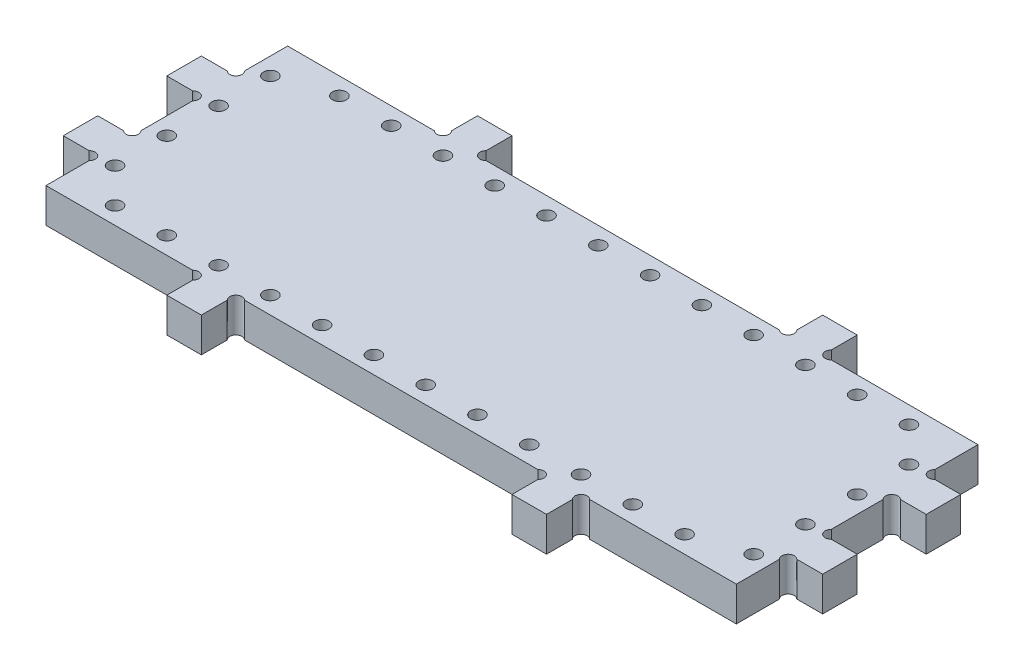
SolidWorks part; units mm, degrees
material "6061 Alloy"
ref_plane "Front" through (0, 0, 0) normal (0, 0, 1) x (1, 0, 0)
ref_plane "Top" through (0, 0, 0) normal (0, 1, 0) x (1, 0, 0)
ref_plane "Right" through (0, 0, 0) normal (1, 0, 0) x (0, 0, -1)
sketch "Sketch2" plane through (0, 0, 0) normal (0, 1, 0) x (1, 0, 0)
  line L1 (-127, -44.45) -> (127, -44.45)
  line L2 (-127, -44.45) -> (-127, 44.45)
  line L3 (-127, 44.45) -> (127, 44.45)
  line L4 (127, -44.45) -> (127, 44.45)
  line L5 (-127, -44.45) -> (127, 44.45) construction
  line L6 (-127, 44.45) -> (127, -44.45) construction
  point P0 (0, 0)
  dimension "D1" = 254
  dimension "D2" = 88.9
extrude "Rectangle Extrusion" add sketch "Sketch2" along normal blind 12.7
sketch "Sketch4" plane through (0, 0, 44.45) normal (0, 0, 1) x (1, 0, 0)
  line L0 (-127, 12.7) -> (-63.5, 12.7) construction
  line L1 (-127, 12.7) -> (127, 12.7) construction
  line L2 (-63.5, 12.7) -> (-63.5, 6.35) construction
  line L3 (-127, 0) -> (127, 0) construction
  line L4 (-57.15, 12.7) -> (-69.85, 12.7)
  line L5 (-57.15, 12.7) -> (-57.15, 0)
  line L6 (-57.15, 0) -> (-69.85, 0)
  line L7 (-69.85, 12.7) -> (-69.85, 0)
  line L8 (-57.15, 12.7) -> (-69.85, 0) construction
  line L9 (-57.15, 0) -> (-69.85, 12.7) construction
  line L10 (0, 12.7) -> (0, 0) construction
  line L11 (57.15, 0) -> (69.85, 0)
  line L12 (69.85, 12.7) -> (69.85, 0)
  line L13 (57.15, 12.7) -> (69.85, 12.7)
  line L14 (57.15, 12.7) -> (57.15, 0)
  dimension "D1" = 63.5
  dimension "D2" = 6.35
  dimension "D3" = 12.7
extrude "Front Face Tabs" add sketch "Sketch4" along normal blind 12.7
mirror "Mirror Rear Face Tabs" about plane through (0, 0, 0) normal (0, 0, 1) of "Front Face Tabs"
sketch "Sketch6" plane through (0, 12.7, 0) normal (0, 1, 0) x (1, 0, 0)
  line L0 (-69.85, 44.45) -> (-127, 44.45) construction
  line L1 (-69.85, 57.15) -> (-69.85, 44.45) construction
  line L2 (-63.5, 57.15) -> (-63.5, 50.1421) construction
  line L3 (-57.15, 57.15) -> (-69.85, 57.15) construction
  line L4 (0, -6.985) -> (0, 6.985) construction
  line L5 (-6.985, 0) -> (6.985, 0) construction
  circle A0 centre (-71.4375, 46.0375) radius 2.2454
  circle A1 centre (-55.5625, 46.0375) radius 2.2454
  circle A2 centre (55.5625, 46.0375) radius 2.2454
  circle A3 centre (71.4375, 46.0375) radius 2.2454
  circle A4 centre (71.4375, -46.0375) radius 2.2454
  circle A5 centre (55.5625, -46.0375) radius 2.2454
  circle A6 centre (-55.5625, -46.0375) radius 2.2454
  circle A7 centre (-71.4375, -46.0375) radius 2.2454
  dimension "D1" = 1.5875
  dimension "D3" = 4.4907
  dimension "D2" = 1.5875
extrude "Tab Curve Front Back" cut sketch "Sketch6" against normal up to surface (12.7 mm away) up to face at (0, 0, 0)
sketch "Sketch7" plane through (127, 0, 0) normal (1, 0, 0) x (0, 0, -1)
  line L0 (-44.45, 12.7) -> (-19.05, 12.7) construction
  line L1 (-44.45, 12.7) -> (44.45, 12.7) construction
  line L2 (-19.05, 12.7) -> (-19.05, 0) construction
  line L3 (66.3575, 0) -> (-66.3575, 0) construction
  line L4 (0, 6.985) -> (0, -6.985) construction
  line L5 (-25.4, 12.7) -> (-12.7, 12.7)
  line L6 (-25.4, 12.7) -> (-25.4, 0)
  line L7 (-25.4, 0) -> (-12.7, 0)
  line L8 (-12.7, 12.7) -> (-12.7, 0)
  line L9 (-25.4, 12.7) -> (-12.7, 0) construction
  line L10 (-25.4, 0) -> (-12.7, 12.7) construction
  line L11 (25.4, 0) -> (12.7, 0)
  line L12 (12.7, 12.7) -> (12.7, 0)
  line L13 (25.4, 12.7) -> (12.7, 12.7)
  line L14 (25.4, 12.7) -> (25.4, 0)
  point P5 (-19.05, 6.35)
  dimension "D1" = 25.4
  dimension "D2" = 12.7
extrude "Right Face Tabs" add sketch "Sketch7" along normal blind 12.7
mirror "Mirror Left Face Tabs" about plane through (0, 0, 0) normal (1, 0, 0) of "Right Face Tabs"
sketch "Sketch8" plane through (0, 12.7, 0) normal (0, 1, 0) x (1, 0, 0)
  line L0 (139.7, 25.4) -> (127, 25.4) construction
  line L1 (127, 25.4) -> (127, 44.45) construction
  line L2 (139.7, 19.05) -> (126.2032, 19.05) construction
  line L3 (139.7, 25.4) -> (139.7, 12.7) construction
  line L4 (-6.985, 0) -> (6.985, 0) construction
  line L5 (0, -6.985) -> (0, 6.985) construction
  circle A0 centre (128.5875, 26.9875) radius 2.2454
  circle A1 centre (128.5875, 11.1125) radius 2.2454
  circle A2 centre (128.5875, -11.1125) radius 2.2454
  circle A3 centre (128.5875, -26.9875) radius 2.2454
  circle A4 centre (-128.5875, -26.9875) radius 2.2454
  circle A5 centre (-128.5875, -11.1125) radius 2.2454
  circle A6 centre (-128.5875, 11.1125) radius 2.2454
  circle A7 centre (-128.5875, 26.9875) radius 2.2454
  dimension "D3" = 4.4907
  dimension "D1" = 1.5875
  dimension "D2" = 1.5875
extrude "Tab Curve Left Right" cut sketch "Sketch8" against normal up to surface (12.7 mm away) up to face at (0, 0, 0)
sketch "Sketch9" plane through (0, 0, 0) normal (0, -1, 0) x (1, 0, 0)
  circle A0 centre (-107.95, 38.1) radius 2.5527
  circle A1 centre (-120.65, 25.4) radius 2.5527
  circle A2 centre (-120.65, 6.35) radius 2.5527
  circle A3 centre (-120.65, -12.7) radius 2.5527
  circle A4 centre (-120.65, -31.75) radius 2.5527
  circle A5 centre (-88.9, 38.1) radius 2.5527
  circle A6 centre (-69.85, 38.1) radius 2.5527
  circle A7 centre (-50.8, 38.1) radius 2.5527
  circle A8 centre (-31.75, 38.1) radius 2.5527
  circle A9 centre (-12.7, 38.1) radius 2.5527
  circle A10 centre (6.35, 38.1) radius 2.5527
  circle A11 centre (25.4, 38.1) radius 2.5527
  circle A12 centre (44.45, 38.1) radius 2.5527
  circle A13 centre (63.5, 38.1) radius 2.5527
  circle A14 centre (82.55, 38.1) radius 2.5527
  circle A15 centre (101.6, 38.1) radius 2.5527
  circle A32 centre (107.95, -38.1) radius 2.5527
  circle A33 centre (120.65, -25.4) radius 2.5527
  circle A34 centre (120.65, -6.35) radius 2.5527
  circle A35 centre (120.65, 12.7) radius 2.5527
  circle A36 centre (120.65, 31.75) radius 2.5527
  circle A37 centre (88.9, -38.1) radius 2.5527
  circle A38 centre (69.85, -38.1) radius 2.5527
  circle A39 centre (50.8, -38.1) radius 2.5527
  circle A40 centre (31.75, -38.1) radius 2.5527
  circle A41 centre (12.7, -38.1) radius 2.5527
  circle A42 centre (-6.35, -38.1) radius 2.5527
  circle A43 centre (-25.4, -38.1) radius 2.5527
  circle A44 centre (-44.45, -38.1) radius 2.5527
  circle A45 centre (-63.5, -38.1) radius 2.5527
  circle A46 centre (-82.55, -38.1) radius 2.5527
  circle A47 centre (-101.6, -38.1) radius 2.5527
  point P64 (-127, 44.45)
  point P65 (127, -44.45)
extrude "Nut Strips Cut" cut sketch "Sketch9" against normal through all
